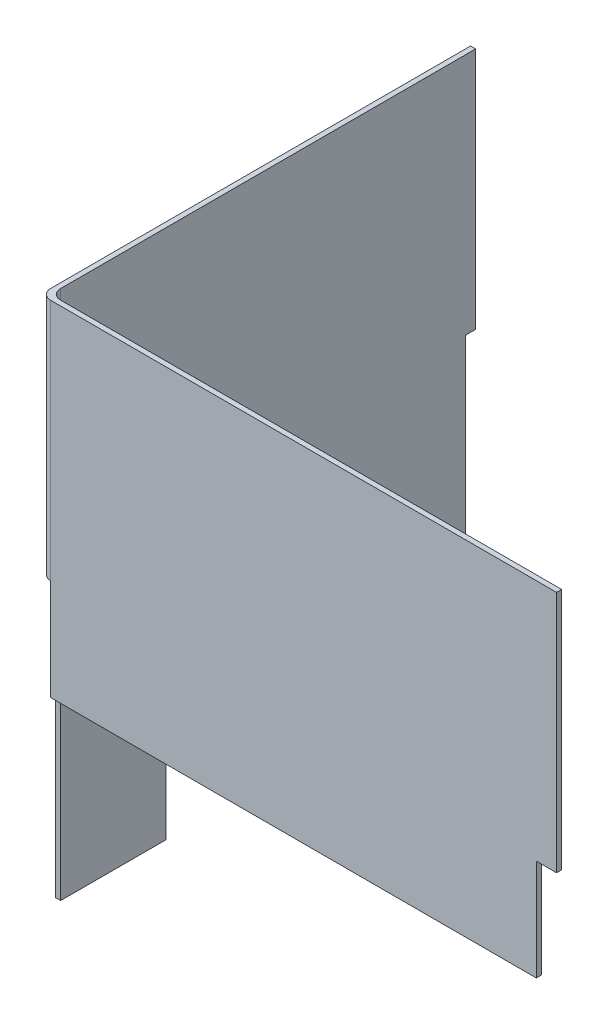
SolidWorks part; units mm, degrees
ref_plane "Front Plane" through (0, 0, 0) normal (0, 0, 1) x (1, 0, 0)
ref_plane "Top Plane" through (0, 0, 0) normal (0, 1, 0) x (1, 0, 0)
ref_plane "Right Plane" through (0, 0, 0) normal (1, 0, 0) x (0, 0, -1)
sketch "Sketch1" plane through (0, 0, 0) normal (0, 0, 1) x (1, 0, 0)
  line L0 (-283.9473, 0) -> (283.9473, 0) construction
  line L1 (0, -177.7291) -> (0, 177.7291) construction
  line L2 (-146.05, -133.9374) -> (-146.05, 133.9374) construction
  line L3 (146.05, -133.0057) -> (146.05, 133.0057) construction
  line L4 (-196.85, -175.4109) -> (-196.85, 175.4109) construction
  line L5 (-146.05, -114.3) -> (146.05, -114.3)
  line L6 (-146.05, -114.3) -> (-146.05, 0)
  line L7 (-146.05, 0) -> (146.05, 0) construction
  line L8 (146.05, -114.3) -> (146.05, 0)
  line L9 (-146.05, -114.3) -> (146.05, 0) construction
  line L10 (-146.05, 0) -> (146.05, -114.3) construction
  line L11 (196.85, -175.4109) -> (196.85, 175.4109) construction
  line L13 (-196.85, 0) -> (-196.85, 152.4)
  line L14 (-196.85, 152.4) -> (196.85, 152.4)
  line L16 (196.85, 0) -> (196.85, 152.4)
  line L17 (-196.85, 0) -> (-146.05, 0)
  line L18 (196.85, 0) -> (146.05, 0)
  point P0 (0, -57.15)
  point P4 (0, 0)
  point P8 (0, 0)
  point P11 (-146.05, 0)
  point P14 (146.05, 0)
  point P21 (-196.85, 0)
  point P28 (0, 152.4)
  dimension "D1" = 146.05
  dimension "D2" = 146.05
  dimension "D3" = 114.3
  dimension "D4" = 292.1
  dimension "D5" = 114.3
  dimension "D6" = 196.85
  dimension "D7" = 152.4
sketch "Sketch4" plane through (0, 0, 0) normal (0, 1, 0) x (1, 0, 0)
  line L0 (-212.9572, 0) -> (212.9572, 0) construction
  line L1 (0, -169.0165) -> (0, 169.0165) construction
  line L2 (-208.5099, 127) -> (208.5099, 127) construction
  line L3 (-152.4, -178.289) -> (-152.4, 178.289) construction
  line L4 (152.4, -178.289) -> (152.4, 178.289) construction
  line L5 (-208.5099, -127) -> (208.5099, -127) construction
  line L9 (-149.225, -127) -> (165.1, -127)
  line L11 (-155.575, 139.7) -> (-155.575, -120.65)
  line L12 (-158.75, -130.175) -> (-158.75, 139.7) construction
  line L13 (-158.75, 139.7) -> (-155.575, 139.7)
  line L17 (165.1, -127) -> (165.1, -130.175)
  line L18 (-158.75, -130.175) -> (168.275, -130.175) construction
  line L19 (-155.575, -127) -> (165.1, -127) construction
  line L20 (-158.75, 139.7) -> (168.275, 139.7) construction
  line L21 (-155.575, -127) -> (-155.575, 136.525) construction
  line L22 (-155.575, 136.525) -> (165.1, 136.525) construction
  line L23 (-281.7923, 133.35) -> (281.7923, 133.35) construction
  line L24 (165.1, -127) -> (165.1, 136.525) construction
  line L25 (-165.1, -172.6871) -> (-165.1, 172.6871) construction
  line L26 (168.275, -130.175) -> (168.275, 139.7) construction
  line L27 (-281.7923, -133.35) -> (281.7923, -133.35) construction
  line L41 (-152.4, -130.175) -> (165.1, -130.175)
  line L42 (-158.75, 139.7) -> (-158.75, -123.825)
  arc A0 (-149.225, -127) -> (-155.575, -120.65) centre (-149.225, -120.65) cw
  arc A1 (-158.75, -123.825) -> (-152.4, -130.175) centre (-152.4, -123.825) ccw
  point P4 (0, 0)
  point P8 (0, 0)
  point P11 (0, 127)
  point P14 (-152.4, 0)
  point P18 (-155.575, -178.289)
  point P19 (-155.575, 178.289)
  point P22 (-208.5099, 134.62)
  point P23 (208.5099, 134.62)
  point P35 (-155.575, -127)
  point P40 (0, 133.35)
  point P43 (-165.1, 0)
  dimension "D4" = 3.175
  dimension "D8" = 6.35
  dimension "D9" = 6.35
  dimension "D3" = 3.175
  dimension "D5" = 6.35
  dimension "D1" = 127
  dimension "D2" = 152.4
  dimension "D6" = 6.35
  dimension "D7" = 12.7
  dimension "D10" = 12.7
extrude "Boss-Extrude2" add sketch "Sketch4" along normal blind 152.4
sketch "Sketch5" plane through (0, 0, 130.175) normal (0, 0, 1) x (1, 0, 0)
  line L0 (-233.4524, 0) -> (233.4524, 0) construction
  line L2 (0, -170.5083) -> (0, 170.5083) construction
  line L8 (-228.46, -31.75) -> (215.76, -31.75) construction
  line L9 (0, -183.1866) -> (0, 183.1866) construction
  line L11 (165.1, 152.4) -> (165.1, 0) construction
  line L12 (-152.4, -63.5) -> (152.4, -63.5)
  line L13 (-152.4, -63.5) -> (-152.4, 0)
  line L14 (-152.4, 0) -> (152.4, 0)
  line L15 (152.4, -63.5) -> (152.4, 0)
  line L16 (-152.4, -63.5) -> (152.4, 0) construction
  line L17 (-152.4, 0) -> (152.4, -63.5) construction
  point P4 (0, 0)
  point P8 (0, 0)
  point P11 (0, 0)
  point P17 (0, -31.75)
  point P19 (0, 0)
  point P20 (0, -31.75)
  point P45 (0, -63.5)
  dimension "D1" = 304.8
  dimension "D2" = 165.1
  dimension "D3" = 31.75
  dimension "D5" = 63.5
extrude "Boss-Extrude3" add sketch "Sketch5" against normal blind 3.175
sketch "Sketch6" plane through (-158.75, 0, 0) normal (-1, 0, 0) x (0, 0, 1)
  line L0 (-225.7102, 0) -> (225.7102, 0) construction
  line L1 (-60.96, -139.7) -> (-60.96, -180.1876) construction
  line L2 (0, -177.5292) -> (0, 177.5292) construction
  line L3 (-214.9401, -203.2) -> (214.9401, -203.2) construction
  line L4 (127, -576.5087) -> (127, 170.1087) construction
  line L5 (-127, -576.5087) -> (-127, 170.1087) construction
  line L6 (-244.0242, -180.1876) -> (244.0242, -180.1876) construction
  line L7 (-219.5188, -78.2066) -> (219.5188, -78.2066) construction
  line L8 (60.96, -139.7) -> (60.96, -180.1876) construction
  line L9 (-60.96, -180.1876) -> (-127, -180.1876) construction
  line L10 (-127, -180.1876) -> (-127, 0) construction
  line L11 (-127, 0) -> (127, 0) construction
  line L12 (127, 0) -> (127, -180.1876) construction
  line L13 (127, -180.1876) -> (60.96, -180.1876) construction
  line L14 (-133.35, -180.1876) -> (-133.35, 0)
  line L15 (-133.35, 0) -> (120.65, 0)
  line L16 (-67.31, -139.7) -> (-67.31, -180.1876)
  line L17 (-67.31, -180.1876) -> (-133.35, -180.1876)
  line L18 (54.61, -139.7) -> (54.61, -180.1876)
  line L19 (120.65, -180.1876) -> (54.61, -180.1876)
  line L20 (120.65, 0) -> (120.65, -180.1876)
  arc A0 (60.96, -139.7) -> (-60.96, -139.7) centre (0, -139.7) ccw construction
  arc A1 (54.61, -139.7) -> (-67.31, -139.7) centre (-6.35, -139.7) ccw
  point P4 (0, 0)
  point P8 (0, 0)
  point P11 (0, -203.2)
  point P14 (127, -203.2)
  point P19 (0, -180.1876)
  point P22 (0, -78.2066)
  dimension "D5" = 121.92
  dimension "D1" = 203.2
  dimension "D2" = 127
  dimension "D3" = 23.0124
  dimension "D4" = 124.9934
  dimension "D6" = 63.5
  dimension "D7" = 2
extrude "Boss-Extrude4" add sketch "Sketch6" against normal blind 3.175
